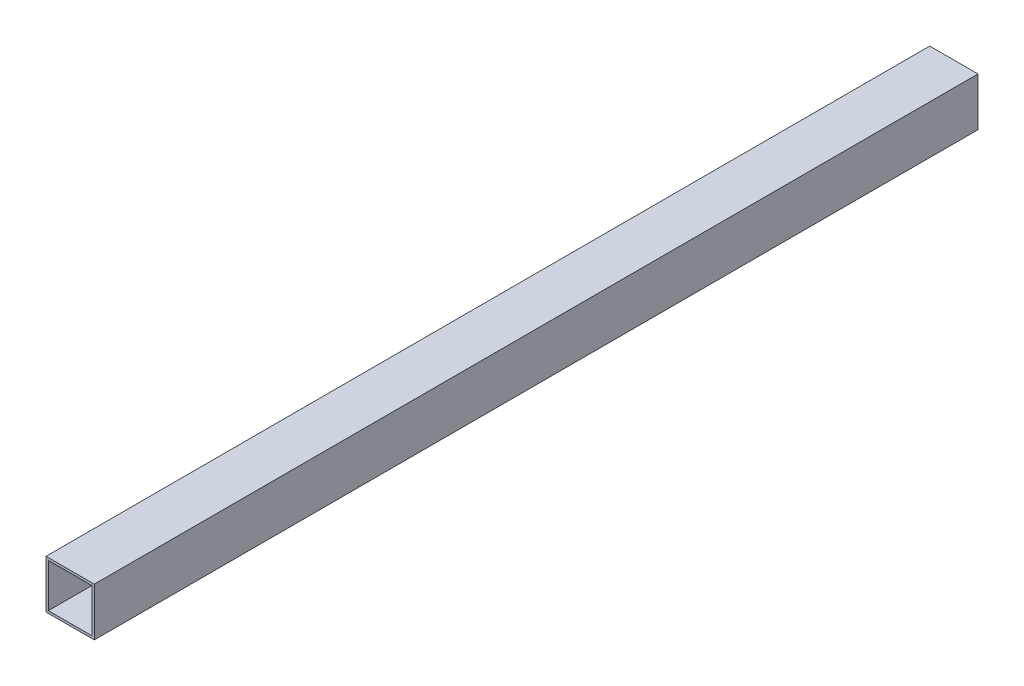
SolidWorks part; units mm, degrees
ref_plane "Plan de face" through (0, 0, 0) normal (0, 0, 1) x (1, 0, 0)
ref_plane "Plan de dessus" through (0, 0, 0) normal (0, 1, 0) x (1, 0, 0)
ref_plane "Plan de droite" through (0, 0, 0) normal (1, 0, 0) x (0, 0, -1)
sketch "Esquisse1" plane through (0, 0, 0) normal (0, 0, 1) x (1, 0, 0)
  line L0 (-450, 450) -> (450, 450)
  line L1 (-500, -500) -> (500, -500)
  line L2 (-500, -500) -> (-500, 500)
  line L3 (-500, 500) -> (500, 500)
  line L4 (500, -500) -> (500, 500)
  line L5 (-500, -500) -> (500, 500) construction
  line L6 (-500, 500) -> (500, -500) construction
  line L7 (450, -450) -> (450, 450)
  line L8 (-450, -450) -> (450, -450)
  line L9 (-450, -450) -> (-450, 450)
  point P0 (0, 0)
  dimension "D1" = 1000
  dimension "D2" = 1000
  dimension "D3" = 50
extrude "Boss.-Extru.1" add sketch "Esquisse1" along normal blind 18300
